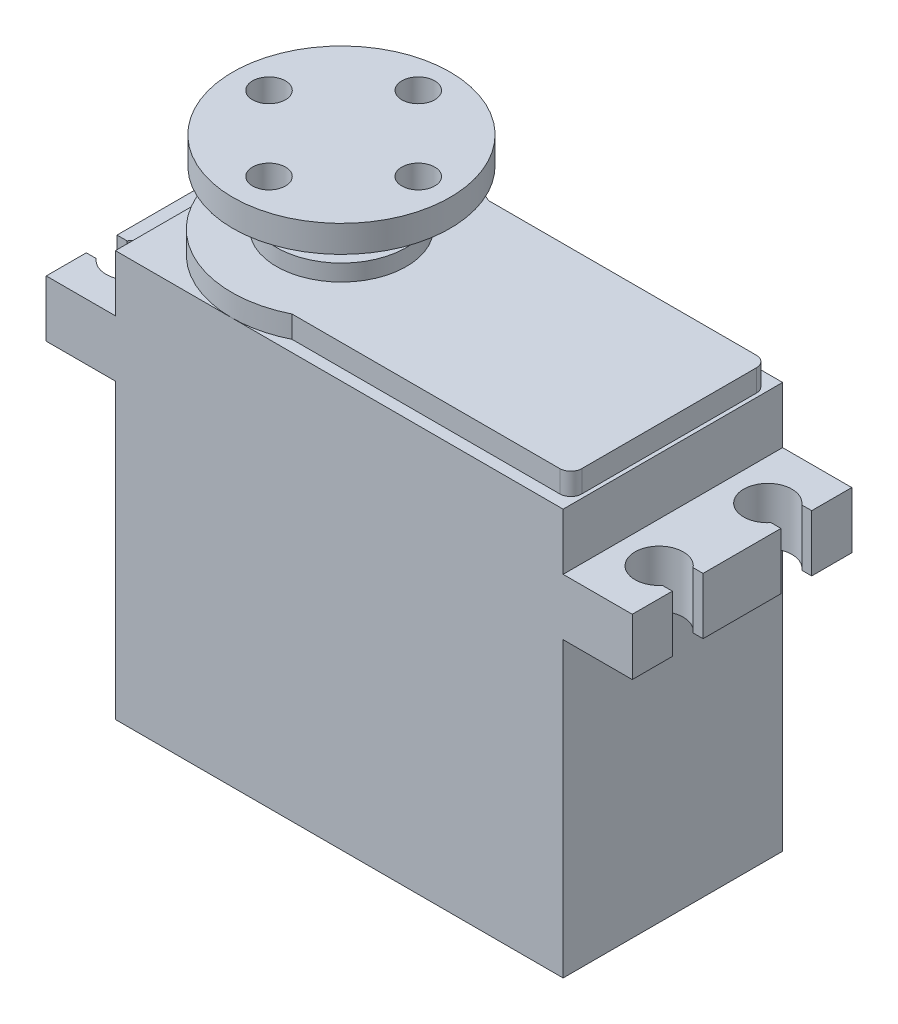
SolidWorks part; units mm, degrees
ref_plane "Front Plane" through (0, 0, 0) normal (0, 0, 1) x (1, 0, 0)
ref_plane "Top Plane" through (0, 0, 0) normal (0, 1, 0) x (1, 0, 0)
ref_plane "Right Plane" through (0, 0, 0) normal (1, 0, 0) x (0, 0, -1)
ref_plane "Plane1" through (0, 0, -10) normal (0, 0, -1) x (-1, 0, 0)
sketch "Sketch9" plane through (0, 0, -10) normal (0, 0, -1) x (-1, 0, 0)
  line L0 (-26.7, 0) -> (26.7, 0)
  line L1 (26.7, 0) -> (26.7, 37)
  line L2 (26.7, 37) -> (-26.7, 37)
  line L3 (-26.7, 37) -> (-26.7, 0)
extrude "Boss-Extrude3" add sketch "Sketch9" against normal blind 20 separate body
sketch "Sketch10" plane through (0, 37, 0) normal (0, 1, 0) x (-1, 0, 0)
  line L0 (-20.05, -8.9526) -> (-20.05, 8.9526)
  line L1 (-20.05, 8.9526) -> (5.3446, 8.9526)
  line L2 (5.3446, -8.9526) -> (-20.05, -8.9526)
  arc A0 (5.3446, 8.9526) -> (5.3446, -8.9526) centre (9.8, 0) cw
extrude "Boss-Extrude4" add sketch "Sketch10" along normal blind 2
ref_plane "Plane2" through (0, 0, 10) normal (0, 0, 1) x (1, 0, 0)
sketch "Sketch15" plane through (0, 0, 10) normal (0, 0, 1) x (1, 0, 0)
  line L0 (-26.7, 0) -> (-20.4, 0)
  line L1 (-20.4, 0) -> (-20.4, 26.7)
  line L2 (-20.4, 26.7) -> (-26.7, 26.7)
  line L3 (-26.7, 26.7) -> (-26.7, 0)
extrude "Cut-Extrude1" cut sketch "Sketch15" against normal through all
sketch "Sketch16" plane through (0, 0, 10) normal (0, 0, 1) x (1, 0, 0)
  line L0 (-20.4, 31.8544) -> (-20.4, 37)
  line L1 (-20.4, 37) -> (-26.7, 37)
  line L2 (-26.7, 37) -> (-26.7, 31.8544)
  line L3 (-26.7, 31.8544) -> (-20.4, 31.8544)
extrude "Cut-Extrude2" cut sketch "Sketch16" against normal through all
sketch "Sketch17" plane through (0, 0, 10) normal (0, 0, 1) x (1, 0, 0)
  line L0 (26.7, 37) -> (20.4, 37)
  line L1 (20.4, 37) -> (20.4, 31.8544)
  line L2 (20.4, 31.8544) -> (26.7, 31.8544)
  line L3 (26.7, 31.8544) -> (26.7, 37)
extrude "Cut-Extrude3" cut sketch "Sketch17" against normal through all
ref_plane "Plane3" through (0, 31.8544, 0) normal (0, 1, 0) x (1, 0, 0)
sketch "Sketch23" plane through (0, 31.8544, 0) normal (0, 1, 0) x (1, 0, 0)
  line L0 (-26.7, -3.55) -> (-26.7, -6.35)
  line L1 (-26.7, -6.35) -> (-25.7971, -6.35)
  line L2 (-25.7971, -3.55) -> (-26.7, -3.55)
  arc A0 (-25.7971, -6.35) -> (-25.7971, -3.55) centre (-24.1, -4.95) cw
extrude "Cut-Extrude4" cut sketch "Sketch23" against normal through all
sketch "Sketch24" plane through (0, 31.8544, 0) normal (0, 1, 0) x (-1, 0, 0)
  line L0 (26.7, -3.55) -> (25.7971, -3.55)
  line L1 (25.7971, -6.35) -> (26.7, -6.35)
  line L2 (26.7, -6.35) -> (26.7, -3.55)
  arc A0 (25.7971, -3.55) -> (25.7971, -6.35) centre (24.1, -4.95) cw
extrude "Cut-Extrude5" cut sketch "Sketch24" against normal through all
sketch "Sketch30" plane through (0, 0, 10) normal (0, 0, 1) x (1, 0, 0)
  line L0 (26.7, 26.7) -> (20.4, 26.7)
  line L1 (20.4, 26.7) -> (20.4, 0)
  line L2 (20.4, 0) -> (26.7, 0)
  line L3 (26.7, 0) -> (26.7, 26.7)
extrude "Cut-Extrude6" cut sketch "Sketch30" against normal through all
sketch "Sketch37" plane through (0, 31.8544, 0) normal (0, 1, 0) x (1, 0, 0)
  line L0 (26.7, 3.55) -> (26.7, 6.35)
  line L1 (26.7, 6.35) -> (25.7971, 6.35)
  line L2 (25.7971, 3.55) -> (26.7, 3.55)
  arc A0 (25.7971, 6.35) -> (25.7971, 3.55) centre (24.1, 4.95) cw
extrude "Cut-Extrude7" cut sketch "Sketch37" against normal through all
sketch "Sketch38" plane through (0, 31.8544, 0) normal (0, 1, 0) x (-1, 0, 0)
  line L0 (-26.7, 3.55) -> (-25.7971, 3.55)
  line L1 (-25.7971, 6.35) -> (-26.7, 6.35)
  line L2 (-26.7, 6.35) -> (-26.7, 3.55)
  arc A0 (-25.7971, 3.55) -> (-25.7971, 6.35) centre (-24.1, 4.95) cw
extrude "Cut-Extrude8" cut sketch "Sketch38" against normal through all
sketch "Sketch40" plane through (0, 0, 0) normal (0, 0, 1) x (1, 0, 0)
  line L0 (-3.8829, 40.5) -> (-9.8, 40.5)
  line L1 (-9.8, 40.5) -> (-9.8, 39)
  line L2 (-9.8, 39) -> (-3.8829, 39)
  line L3 (-3.8829, 39) -> (-3.8829, 40.5)
  line L4 (-9.8, 40.5) -> (-9.8, 39) construction
revolve "Revolve2" add sketch "Sketch40" angle 360 about L1
ref_plane "Plane4" through (0, 0, -4.95) normal (0, 0, -1) x (-1, 0, 0)
sketch "Sketch47" plane through (0, 0, -4.95) normal (0, 0, -1) x (-1, 0, 0)
  line L0 (21.9, 26.7) -> (24.1, 26.7)
  line L1 (24.1, 26.7) -> (24.1, 31.8544)
  line L2 (24.1, 31.8544) -> (21.9, 31.8544)
  line L3 (21.9, 31.8544) -> (21.9, 26.7)
  line L4 (24.1, 26.7) -> (24.1, 31.8544) construction
revolve "Cut-Revolve1" cut sketch "Sketch47" angle 360 about L1
ref_plane "Plane5" through (0, 0, 4.95) normal (0, 0, -1) x (-1, 0, 0)
sketch "Sketch55" plane through (0, 0, 4.95) normal (0, 0, -1) x (-1, 0, 0)
  line L0 (-26.3, 26.7) -> (-24.1, 26.7)
  line L1 (-24.1, 26.7) -> (-24.1, 31.8544)
  line L2 (-24.1, 31.8544) -> (-26.3, 31.8544)
  line L3 (-26.3, 31.8544) -> (-26.3, 26.7)
  line L4 (-24.1, 26.7) -> (-24.1, 31.8544) construction
revolve "Cut-Revolve2" cut sketch "Sketch55" angle 360 about L1
sketch "Sketch64" plane through (0, 0, 4.95) normal (0, 0, -1) x (-1, 0, 0)
  line L0 (21.9, 26.7) -> (24.1, 26.7)
  line L1 (24.1, 26.7) -> (24.1, 31.8544)
  line L2 (24.1, 31.8544) -> (21.9, 31.8544)
  line L3 (21.9, 31.8544) -> (21.9, 26.7)
  line L4 (24.1, 26.7) -> (24.1, 31.8544) construction
revolve "Cut-Revolve3" cut sketch "Sketch64" angle 360 about L1
sketch "Sketch72" plane through (0, 0, -4.95) normal (0, 0, -1) x (-1, 0, 0)
  line L0 (-26.3, 26.7) -> (-24.1, 26.7)
  line L1 (-24.1, 26.7) -> (-24.1, 31.8544)
  line L2 (-24.1, 31.8544) -> (-26.3, 31.8544)
  line L3 (-26.3, 31.8544) -> (-26.3, 26.7)
  line L4 (-24.1, 26.7) -> (-24.1, 31.8544) construction
revolve "Cut-Revolve4" cut sketch "Sketch72" angle 360 about L1
hole_wizard "Ø3.0 (3) Diameter Hole2" positions "Sketch74" profile "Sketch73" hole size "Ø3.0" standard "ANSI Metric"
sketch "Sketch74" plane through (0, 40.5, 0) normal (0, 1, 0) x (1, 0, 0)
  point P0 (-9.8, 0)
sketch "Sketch73" plane through (-9.8, 40.5, 0) normal (1, 0, 0) x (0, 0, 1)
  line L0 (0, 0) -> (0, 1.5)
  line L1 (0, 1.5) -> (1.5, 1.5)
  line L2 (1.5, 1.5) -> (1.5, 0)
  line L5 (1.5, 0) -> (0, 0)
  line L10 (0, 1.5) -> (-1.5, 1.5) construction
  line L11 (0, -6.35) -> (0, 107.95) construction
  dimension "Hole Dia." = 3
  dimension "Hole Depth" = 1.5
  dimension "Drill Angle" = 180
fillet "Fillet1" radius 1 2 edges at (20.05, 38, -8.9526) (20.05, 38, 8.9526)
sketch "Sketch76" plane through (0, 0, 0) normal (0, 0, 1) x (1, 0, 0)
  line L0 (0.1, 46.45) -> (-9.8, 46.45)
  line L1 (-9.8, 46.45) -> (-9.8, 44)
  line L2 (-9.8, 44) -> (0.1, 44)
  line L3 (0.1, 44) -> (0.1, 46.45)
  line L4 (-9.8, 46.45) -> (-9.8, 44) construction
revolve "Revolve3" add sketch "Sketch76" angle 360 about L1
ref_plane "Plane6" through (0, 44, 0) normal (0, -1, 0) x (-1, 0, 0)
sketch "Sketch85" plane through (0, 44, 0) normal (0, -1, 0) x (-1, 0, 0)
  circle A0 centre (9.8, 0) radius 4.5
extrude "Boss-Extrude5" add sketch "Sketch85" along normal blind 2.25
sketch "Sketch86" plane through (0, 41.75, 0) normal (0, -1, 0) x (1, 0, 0)
  circle A0 centre (-9.8, 0) radius 1.5
extrude "Boss-Extrude6" add sketch "Sketch86" along normal blind 1.25
hole_wizard "Ø3.0 (3) Diameter Hole3" positions "Sketch88" profile "Sketch87" hole size "Ø3.0" standard "ANSI Metric"
sketch "Sketch88" plane through (0, 46.45, 0) normal (0, 1, 0) x (1, 0, 0)
  point P0 (-2.9992, 0.1992)
  point P1 (-9.8, -6.6015)
  point P2 (-16.6008, 0.1992)
  point P3 (-9.8, 7)
sketch "Sketch87" plane through (-2.9992, 46.45, -0.1992) normal (1, 0, 0) x (0, 0, 1)
  line L0 (0, 0) -> (0, 46.45)
  line L1 (0, 46.45) -> (1.5, 46.45)
  line L2 (1.5, 46.45) -> (1.5, 0)
  line L5 (1.5, 0) -> (0, 0)
  line L11 (0, -6.35) -> (0, 107.95) construction
  dimension "Thru Hole Dia." = 3
  dimension "Thru Hole Depth" = 46.45
sketch "Sketch89" plane through (0, 0, 0) normal (0, -1, 0) x (1, 0, 0)
  line L4 (20.4, -10) -> (20.4, 10)
  line L5 (20.4, 10) -> (-20.4, 10)
  line L6 (-20.4, 10) -> (-20.4, -10)
  line L7 (-20.4, -10) -> (20.4, -10)
  line L8 (20.4, -10) -> (20.4, 10)
  line L9 (20.4, 10) -> (-20.4, 10)
  line L10 (-20.4, 10) -> (-20.4, -10)
  line L11 (-20.4, -10) -> (20.4, -10)
  dimension "D1" = 0
extrude "Boss-Extrude7" add sketch "Sketch89" against normal blind 10
sketch "Sketch90" plane through (0, 39, 0) normal (0, 1, 0) x (1, 0, 0)
  line L3 (20.05, -7.9526) -> (20.05, 7.9526)
  line L4 (19.05, 8.9526) -> (-5.3446, 8.9526)
  line L5 (-5.3446, -8.9526) -> (19.05, -8.9526)
  line L6 (20.05, -7.9526) -> (20.05, 7.9526)
  line L7 (19.05, 8.9526) -> (-5.3446, 8.9526)
  line L8 (-5.3446, -8.9526) -> (19.05, -8.9526)
  arc A3 (20.05, 7.9526) -> (19.05, 8.9526) centre (19.05, 7.9526) ccw
  arc A4 (-5.3446, 8.9526) -> (-5.3446, -8.9526) centre (-9.8, 0) ccw
  arc A5 (19.05, -8.9526) -> (20.05, -7.9526) centre (19.05, -7.9526) ccw
  arc A6 (20.05, 7.9526) -> (19.05, 8.9526) centre (19.05, 7.9526) ccw
  arc A7 (-5.3446, 8.9526) -> (-5.3446, -8.9526) centre (-9.8, 0) ccw
  arc A8 (19.05, -8.9526) -> (20.05, -7.9526) centre (19.05, -7.9526) ccw
  dimension "D1" = 0
extrude "Boss-Extrude8" add sketch "Sketch90" against normal blind 10
sketch "Sketch91" plane through (0, 40.5, 0) normal (0, 1, 0) x (1, 0, 0)
  circle A0 centre (-9.8, 0) radius 5.9171
extrude "Boss-Extrude9" add sketch "Sketch91" against normal blind 10
